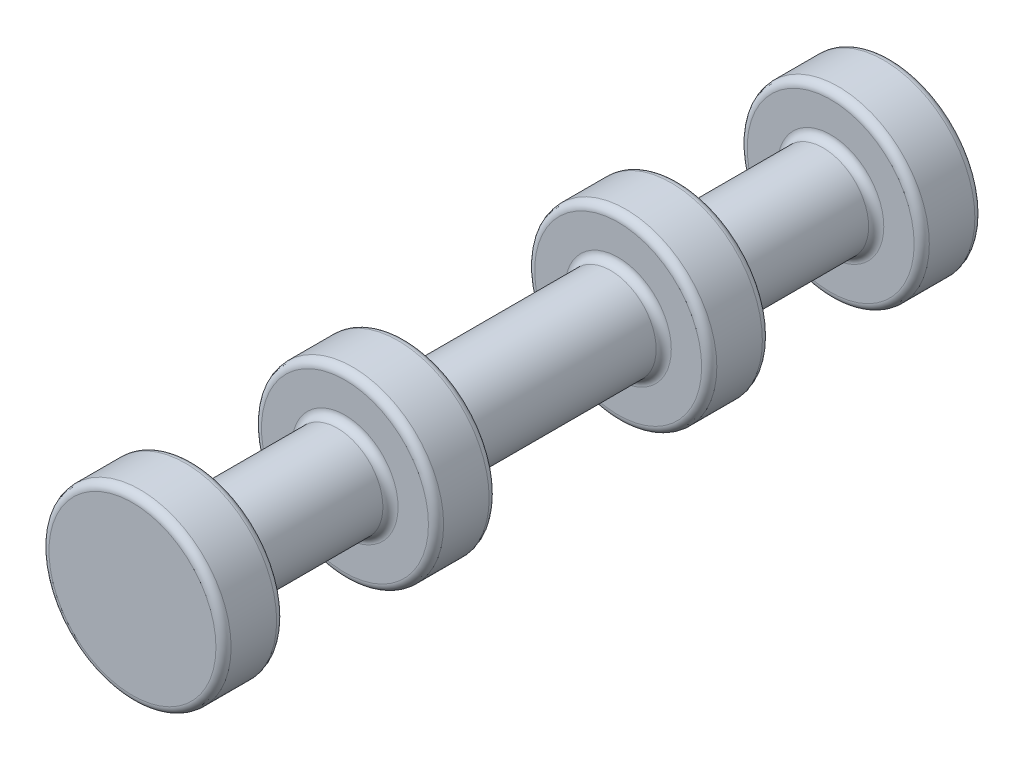
SolidWorks part; units mm, degrees
ref_plane "Front Plane" through (0, 0, 0) normal (0, 0, 1) x (1, 0, 0)
ref_plane "Top Plane" through (0, 0, 0) normal (0, 1, 0) x (1, 0, 0)
ref_plane "Right Plane" through (0, 0, 0) normal (1, 0, 0) x (0, 0, -1)
sketch "Sketch1" plane through (0, 0, 0) normal (0, 1, 0) x (1, 0, 0)
  line L0 (-0.848, 0.674) -> (-0.848, 6.0645) construction
  line L1 (-0.848, -9.7674) -> (-3.598, -9.7674)
  line L2 (-3.848, -9.5174) -> (-3.848, -8.0174)
  line L3 (-3.598, -7.7674) -> (-2.598, -7.7674)
  line L4 (-2.348, -7.5174) -> (-2.348, -3.0174)
  line L5 (-2.598, -2.7674) -> (-3.598, -2.7674)
  line L6 (-3.848, -2.5174) -> (-3.848, -1.0174)
  line L7 (-3.598, -0.7674) -> (-2.598, -0.7674)
  line L8 (-2.348, -0.5174) -> (-2.348, 5.9826)
  line L9 (-2.598, 6.2326) -> (-3.598, 6.2326)
  line L10 (-3.848, 6.4826) -> (-3.848, 7.9826)
  line L11 (-3.598, 8.2326) -> (-2.598, 8.2326)
  line L12 (-2.348, 8.4826) -> (-2.348, 12.9826)
  line L13 (-2.598, 13.2326) -> (-3.598, 13.2326)
  line L14 (-3.848, 13.4826) -> (-3.848, 14.9826)
  line L15 (-3.598, 15.2326) -> (-0.848, 15.2326)
  line L16 (-0.848, -9.7674) -> (-0.848, 15.2326)
  arc A0 (-3.848, 14.9826) -> (-3.598, 15.2326) centre (-3.598, 14.9826) cw
  arc A1 (-3.598, 13.2326) -> (-3.848, 13.4826) centre (-3.598, 13.4826) cw
  arc A2 (-2.348, 12.9826) -> (-2.598, 13.2326) centre (-2.598, 12.9826) ccw
  arc A3 (-2.598, 8.2326) -> (-2.348, 8.4826) centre (-2.598, 8.4826) ccw
  arc A4 (-3.848, 7.9826) -> (-3.598, 8.2326) centre (-3.598, 7.9826) cw
  arc A5 (-3.598, 6.2326) -> (-3.848, 6.4826) centre (-3.598, 6.4826) cw
  arc A6 (-2.348, 5.9826) -> (-2.598, 6.2326) centre (-2.598, 5.9826) ccw
  arc A7 (-2.598, -0.7674) -> (-2.348, -0.5174) centre (-2.598, -0.5174) ccw
  arc A8 (-3.848, -1.0174) -> (-3.598, -0.7674) centre (-3.598, -1.0174) cw
  arc A9 (-3.598, -2.7674) -> (-3.848, -2.5174) centre (-3.598, -2.5174) cw
  arc A10 (-2.348, -3.0174) -> (-2.598, -2.7674) centre (-2.598, -3.0174) ccw
  arc A11 (-2.598, -7.7674) -> (-2.348, -7.5174) centre (-2.598, -7.5174) ccw
  arc A12 (-3.848, -8.0174) -> (-3.598, -7.7674) centre (-3.598, -8.0174) cw
  arc A13 (-3.598, -9.7674) -> (-3.848, -9.5174) centre (-3.598, -9.5174) cw
  point P20 (-3.848, 15.2326)
  point P23 (-3.848, 13.2326)
  point P26 (-2.348, 13.2326)
  point P29 (-2.348, 8.2326)
  point P32 (-3.848, 8.2326)
  point P35 (-3.848, 6.2326)
  point P42 (-3.848, -0.7674)
  point P45 (-3.848, -2.7674)
  point P48 (-2.348, -2.7674)
  point P51 (-2.348, -7.7674)
  point P54 (-3.848, -7.7674)
  point P57 (-3.848, -9.7674)
  dimension "D10" = 0.25
  dimension "D1" = 25
  dimension "D2" = 2
  dimension "D3" = 2
  dimension "D4" = 2
  dimension "D5" = 2
  dimension "D6" = 5
  dimension "D7" = 5
  dimension "D8" = 6
  dimension "D9" = 3
revolve "Revolve1" add sketch "Sketch1" angle 360 about L0
